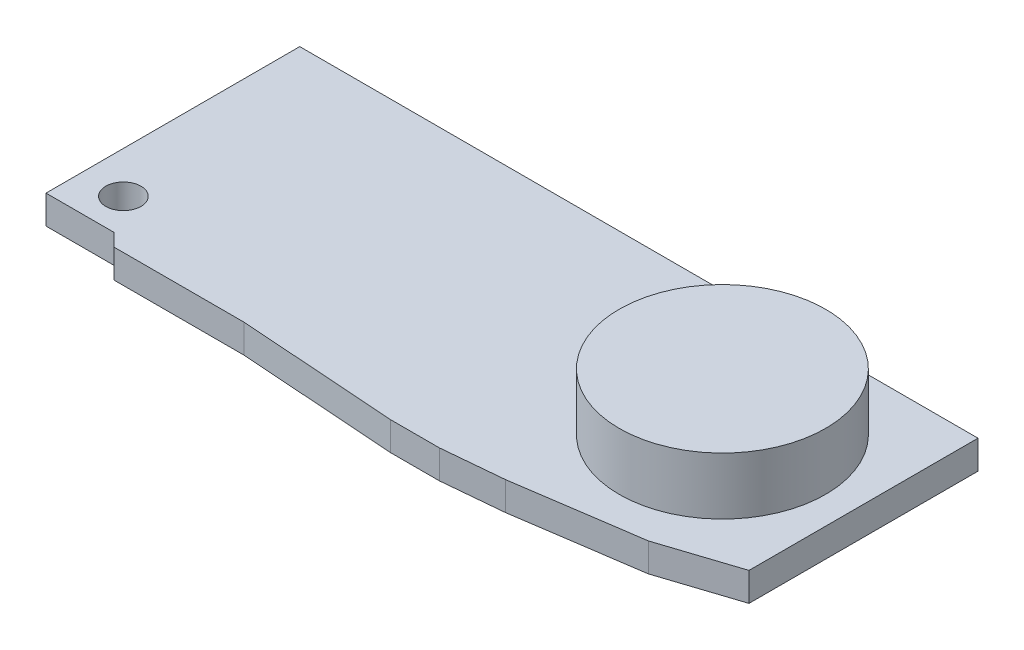
SolidWorks part; units mm, degrees
ref_plane "前视基准面" through (0, 0, 0) normal (0, 0, 1) x (1, 0, 0)
ref_plane "上视基准面" through (0, 0, 0) normal (0, 1, 0) x (1, 0, 0)
ref_plane "右视基准面" through (0, 0, 0) normal (1, 0, 0) x (0, 0, -1)
other "Configuration Table"
sketch "草图1" plane through (0, 0, 0) normal (0, 1, 0) x (1, 0, 0)
  line L0 (-143.8022, 36.4923) -> (1114.7559, 565.7999) construction
  line L1 (-27.4403, -0.7842) -> (20.0074, -0.7842)
  line L2 (0, 0) -> (100, 0) construction
  line L6 (20.0074, -0.7842) -> (20.0074, -16.8048)
  line L7 (-27.4403, -0.7842) -> (-27.4403, -18.5352)
  line L8 (-27.4403, -18.5352) -> (-22.6955, -18.5352)
  line L9 (-22.6955, -18.5352) -> (-21.8024, -19.4284)
  line L10 (-21.8024, -19.4284) -> (-12.7036, -19.4284)
  line L11 (-12.7036, -19.4284) -> (-1.6511, -20.2098)
  line L12 (-1.6511, -20.2098) -> (1.754, -20.2098)
  line L13 (1.754, -20.2098) -> (5.9964, -19.8191)
  line L14 (5.9964, -19.8191) -> (14.7044, -18.5352)
  line L15 (14.7044, -18.5352) -> (20.0074, -16.8048)
  circle A0 centre (-24.5376, -16.0233) radius 1.2293
  circle A1 centre (3.0937, -3.0729) radius 1.1494
  dimension "D3" = 47.4477
extrude "凸台-拉伸1" add sketch "草图1" along normal blind 2
sketch "草图2" plane through (0, 2, 0) normal (0, 1, 0) x (1, 0, 0)
  circle A0 centre (10.8646, -9.5217) radius 7.2213
extrude "凸台-拉伸2" add sketch "草图2" along normal blind 4
sketch "草图3" plane through (0, 0, 0) normal (0, -1, 0) x (-1, 0, 0)
  line L1 (25.6377, -8.8934) -> (22.9926, -8.8934)
  line L2 (25.6377, -8.8934) -> (25.6377, -5.7524)
  line L3 (25.6377, -5.7524) -> (22.9926, -5.7524)
  line L4 (22.9926, -8.8934) -> (22.9926, -5.7524)
  line L5 (10.4945, -9.2571) -> (8.6099, -9.2571)
  line L6 (10.4945, -9.2571) -> (10.4945, -6.2153)
  line L7 (10.4945, -6.2153) -> (8.6099, -6.2153)
  line L8 (8.6099, -9.2571) -> (8.6099, -6.2153)
  line L9 (1.9641, -9.5878) -> (0, -9.5878)
  line L10 (1.9641, -9.5878) -> (1.9641, -6.2153)
  line L11 (1.9641, -6.2153) -> (0, -6.2153)
  line L12 (0, -9.5878) -> (0, -6.2153)
  line L13 (-9.7405, -9.5878) -> (-12.3194, -9.5878)
  line L14 (-9.7405, -9.5878) -> (-9.7405, -6.579)
  line L15 (-9.7405, -6.579) -> (-12.3194, -6.579)
  line L16 (-12.3194, -9.5878) -> (-12.3194, -6.579)
extrude "凸台-拉伸3" add sketch "草图3" along normal blind 2.5
equation "\"SC\"= 1"
